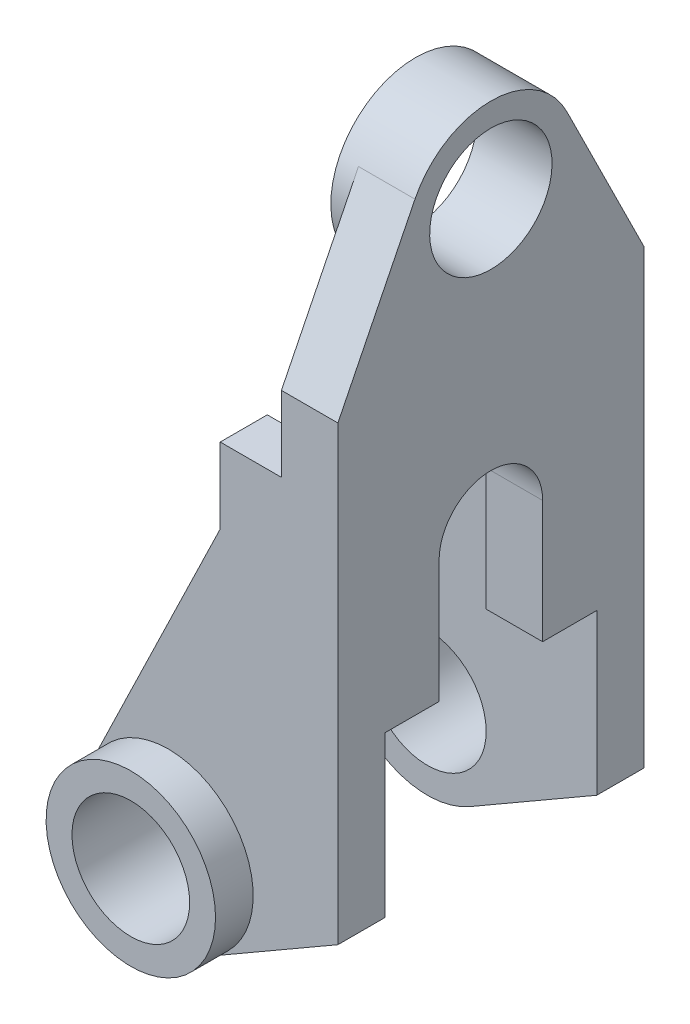
SolidWorks part; units mm, degrees
ref_plane "Front Plane" through (0, 0, 0) normal (0, 0, 1) x (1, 0, 0)
ref_plane "Top Plane" through (0, 0, 0) normal (0, 1, 0) x (1, 0, 0)
ref_plane "Right Plane" through (0, 0, 0) normal (1, 0, 0) x (0, 0, -1)
sketch "Sketch1" plane through (0, 0, 0) normal (0, 0, 1) x (1, 0, 0)
  line L1 (27.1996, 56.1532) -> (27.1996, 72.1532)
  line L2 (27.1996, 72.1532) -> (52.1996, 72.1532)
  line L3 (52.1996, 72.1532) -> (52.1996, -7.8468)
  line L4 (52.1996, -7.8468) -> (25.1996, -23.4353)
  line L5 (27.1996, 56.1532) -> (0, 0)
  arc A0 (25.1996, -23.4353) -> (0, 0) centre (16.1996, -7.8468) cw
  dimension "D3" = 18
  dimension "D1" = 25
  dimension "D2" = 64
  dimension "D4" = 16
  dimension "D5" = 36
extrude "Boss-Extrude1" add sketch "Sketch1" along normal mid plane 10
sketch "Sketch2" plane through (0, 0, 5) normal (0, 0, 1) x (1, 0, 0)
  arc A0 (0, 0) -> (25.1996, -23.4353) centre (16.1996, -7.8468) ccw construction
  arc A1 (0, 0) -> (25.1996, -23.4353) centre (16.1996, -7.8468) ccw
  circle A2 centre (16.1996, -7.8468) radius 18
  circle A3 centre (16.1996, -7.8468) radius 12.5
  arc M2 (0, 0) -> (25.1996, -23.4353) centre (16.1996, -7.8468) ccw
  dimension "D1" = 36
  dimension "D2" = 25
extrude "Boss-Extrude2" add sketch "Sketch2" along normal blind 8 contours A2 A3 M2
sketch "Sketch3" plane through (0, 0, 5) normal (0, 0, 1) x (1, 0, 0)
  circle A1 centre (16.1996, -7.8468) radius 12.5
  circle A2 centre (16.1996, -7.8468) radius 12.5
  dimension "D1" = 0
extrude "Cut-Extrude1" cut sketch "Sketch3" against normal up to next
sketch "Sketch5" plane through (52.1996, 0, 0) normal (1, 0, 0) x (0, 0, -1)
  line L0 (-5, 88.1532) -> (60, 88.1532)
  line L1 (60, 88.1532) -> (43.624, 121.1543)
  line L2 (11.376, 121.1543) -> (-5, 88.1532)
  line L9 (50, 88.1532) -> (-5, 88.1532)
  line L15 (60, 88.1532) -> (60, 72.1532)
  line L16 (60, 72.1532) -> (-5, 72.1532)
  line L18 (-5, 72.1532) -> (-5, 88.1532)
  line L19 (5, 72.1532) -> (5, 26.1532)
  line L20 (5, 56.1532) -> (5, 0) construction
  line L21 (5, 26.1532) -> (16.5, 26.1532)
  line L22 (38.5, 26.1532) -> (50, 26.1532)
  line L23 (50, 26.1532) -> (50, 72.1532)
  line L24 (50, 72.1532) -> (5, 72.1532)
  line L25 (60, 72.1532) -> (60, 88.1532)
  line L26 (38.5, 26.1532) -> (38.5, 52.1532)
  line L27 (16.5, 52.1532) -> (16.5, 26.1532)
  arc A0 (43.624, 121.1543) -> (11.376, 121.1543) centre (27.5, 113.1532) ccw
  circle A1 centre (27.5, 113.1532) radius 13
  arc A3 (43.624, 121.1543) -> (11.376, 121.1543) centre (27.5, 113.1532) cw
  arc A6 (38.5, 52.1532) -> (16.5, 52.1532) centre (27.5, 52.1532) ccw
  dimension "D1" = 18
  dimension "D4" = 26
  dimension "D2" = 65
  dimension "D3" = 25
  dimension "D5" = 16
  dimension "D6" = 45
  dimension "D8" = 22
  dimension "D9" = 20
  dimension "D7" = 46
extrude "Boss-Extrude3" add sketch "Sketch5" against normal blind 12
sketch "Sketch6" plane through (52.1996, 0, 0) normal (1, 0, 0) x (0, 0, -1)
  circle A3 centre (27.5, 113.1532) radius 13 construction
  circle A4 centre (27.5, 113.1532) radius 13
  circle A5 centre (27.5, 113.1532) radius 18
  dimension "D1" = 36
extrude "Boss-Extrude4" add sketch "Sketch6" against normal blind 16
ref_plane "Plane1" through (0, 0, -27.5) normal (0, 0, 1) x (1, 0, 0)
mirror "Mirror1" about plane through (0, 0, -27.5) normal (0, 0, 1) of "Boss-Extrude2", "Boss-Extrude1"
sketch "Sketch7" plane through (0, 0, -60) normal (0, 0, -1) x (-1, 0, 0)
  circle A1 centre (-16.1996, -7.8468) radius 12.5
  circle A2 centre (-16.1996, -7.8468) radius 12.5
  dimension "D1" = 0
extrude "Cut-Extrude2" cut sketch "Sketch7" against normal up to next
sketch "Sketch8" plane through (40.1996, 0, 0) normal (-1, 0, 0) x (0, 0, 1)
  line L0 (-5, 26.1532) -> (-16.5, 26.1532) construction
  line L1 (-38.5, 26.1532) -> (-38.5, 52.1532) construction
  line L2 (-38.5, 26.1532) -> (-50, 26.1532) construction
  line L3 (-5, 72.1532) -> (-5, 26.1532) construction
  line L4 (-16.5, 52.1532) -> (-16.5, 26.1532) construction
  line L5 (-60, 72.1532) -> (5, 72.1532) construction
  line L6 (-50, 26.1532) -> (-50, 72.1532) construction
  line L7 (-5, 26.1532) -> (-16.5, 26.1532)
  line L8 (-38.5, 26.1532) -> (-38.5, 52.1532)
  line L9 (-38.5, 26.1532) -> (-50, 26.1532)
  line L10 (-5, 72.1532) -> (-5, 26.1532)
  line L11 (-16.5, 52.1532) -> (-16.5, 26.1532)
  line L12 (-50, 72.1532) -> (-5, 72.1532)
  line L13 (-50, 26.1532) -> (-50, 72.1532)
  arc A0 (-16.5, 52.1532) -> (-38.5, 52.1532) centre (-27.5, 52.1532) ccw construction
  arc A1 (-16.5, 52.1532) -> (-38.5, 52.1532) centre (-27.5, 52.1532) ccw
extrude "Boss-Extrude5" add sketch "Sketch8" against normal up to surface (12 mm away) up to face at (52.1996, 54.1533, -27.5)
sketch "Sketch9" plane through (52.1996, 0, 0) normal (1, 0, 0) x (0, 0, -1)
equation "\"D2@Sketch5\"=45+10+10"
